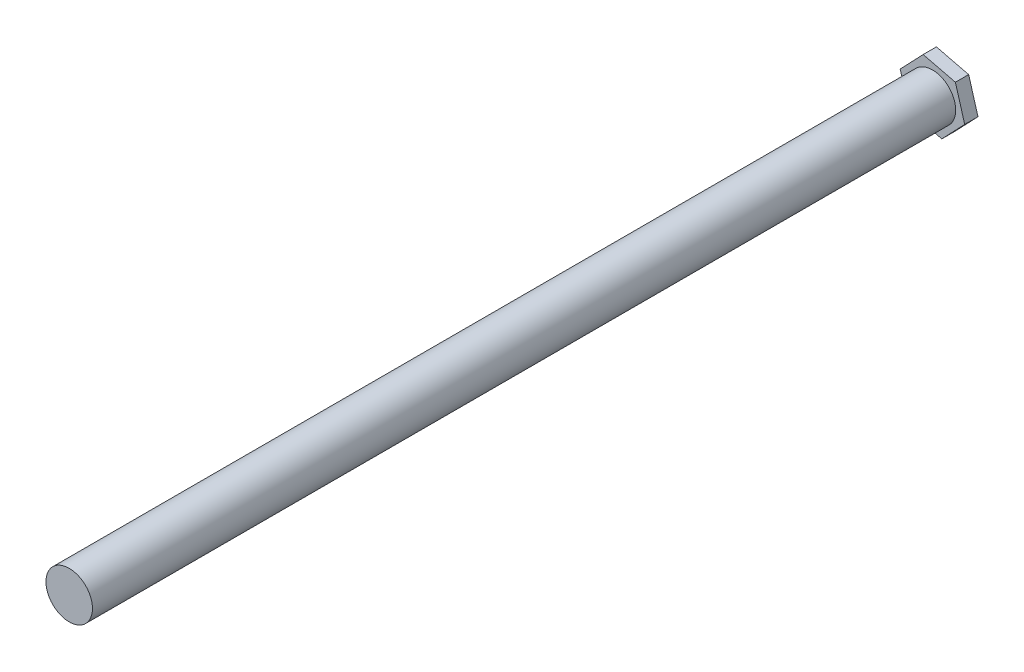
SolidWorks part; units mm, degrees
ref_plane "Front Plane" through (0, 0, 0) normal (0, 0, 1) x (1, 0, 0)
ref_plane "Top Plane" through (0, 0, 0) normal (0, 1, 0) x (1, 0, 0)
ref_plane "Right Plane" through (0, 0, 0) normal (1, 0, 0) x (0, 0, -1)
sketch "Sketch1" plane through (0, 0, 0) normal (0, 0, 1) x (1, 0, 0)
  circle A0 centre (0, 0) radius 0.889
  dimension "D1" = 1.778
extrude "Boss-Extrude1" add sketch "Sketch1" along normal blind 33.02
sketch "Sketch2" plane through (0, 0, 0) normal (0, 0, -1) x (-1, 0, 0)
  line L1 (0.877, -0.9186) -> (1.234, 0.3002)
  line L2 (1.234, 0.3002) -> (0.357, 1.2188)
  line L3 (0.357, 1.2188) -> (-0.877, 0.9186)
  line L4 (-0.877, 0.9186) -> (-1.234, -0.3002)
  line L5 (-1.234, -0.3002) -> (-0.357, -1.2188)
  line L6 (-0.357, -1.2188) -> (0.877, -0.9186)
  circle A0 centre (0, 0) radius 1.0999 construction
  dimension "D1" = 1.27
extrude "Boss-Extrude3" add sketch "Sketch2" along normal blind 0.508
